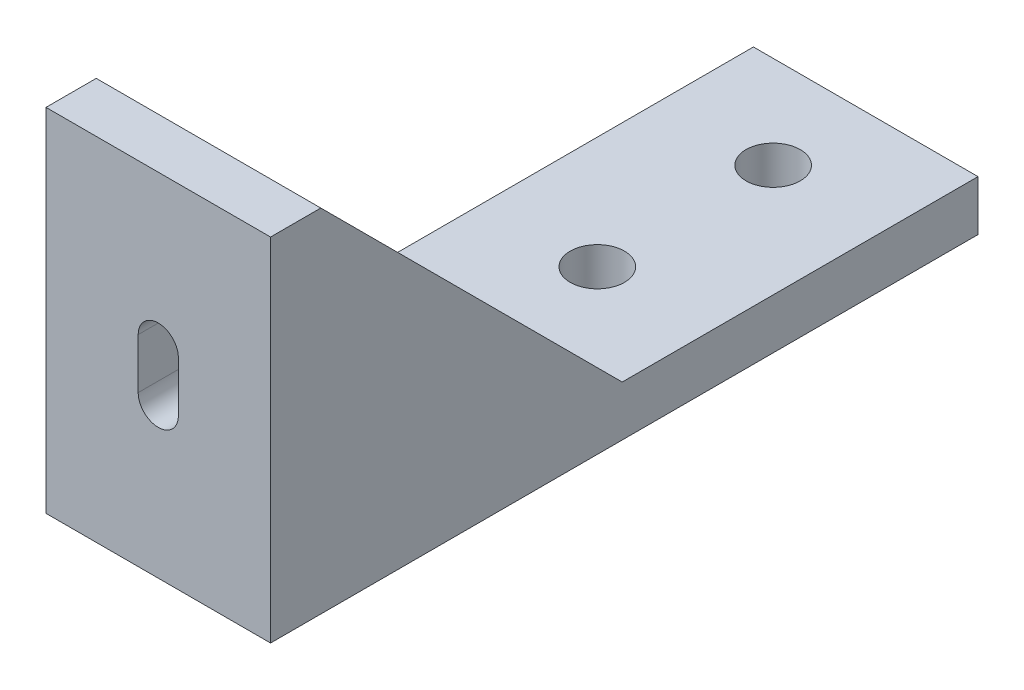
SolidWorks part; units mm, degrees
ref_plane "Front Plane" through (0, 0, 0) normal (0, 0, 1) x (1, 0, 0)
ref_plane "Top Plane" through (0, 0, 0) normal (0, 1, 0) x (1, 0, 0)
ref_plane "Right Plane" through (0, 0, 0) normal (1, 0, 0) x (0, 0, -1)
sketch "Sketch1" plane through (0, 0, 0) normal (0, 1, 0) x (1, 0, 0)
  line L0 (0.6663, -42.8738) -> (-10.5097, -42.8738)
  line L1 (-10.5097, -15.8168) -> (-10.5097, -42.8738)
  line L2 (0.6663, -42.8738) -> (11.8423, -42.8738)
  line L3 (11.8423, -42.8738) -> (11.8423, 42.5406)
  line L4 (11.8423, 42.5406) -> (-10.5097, 42.5406)
  line L5 (-10.5097, -15.8168) -> (-10.5097, 42.5406)
  circle A0 centre (0.6663, 31.3196) radius 2.7
  circle A1 centre (0.6663, 14.2508) radius 2.7
extrude "Boss-Extrude1" add sketch "Sketch1" along normal blind 5
sketch "Sketch2" plane through (0, 5, 0) normal (0, 1, 0) x (1, 0, 0)
  line L0 (-10.5097, 42.5406) -> (-10.5097, -42.8738) construction
  line L1 (11.8423, -42.8738) -> (-10.5097, -42.8738)
  line L2 (11.8423, -42.8738) -> (11.8423, -37.8738)
  line L3 (11.8423, -37.8738) -> (-10.5097, -37.8738)
  line L4 (-10.5097, -42.8738) -> (-10.5097, -37.8738)
extrude "Boss-Extrude2" add sketch "Sketch2" along normal blind 30
sketch "Sketch3" plane through (0, 0, 37.8738) normal (0, 0, -1) x (-1, 0, 0)
  line L0 (-11.8423, 35) -> (10.5097, 35) construction
  line L1 (-11.8423, 5) -> (-11.8423, 35)
  line L3 (-2.6663, 20) -> (-2.6663, 15)
  line L4 (1.3337, 20) -> (1.3337, 15)
  arc A0 (1.3337, 20) -> (-2.6663, 20) centre (-0.6663, 20) ccw
  arc A1 (-2.6663, 15) -> (1.3337, 15) centre (-0.6663, 15) ccw
  point P0 (-0.6663, 35)
  point P1 (-11.8423, 5)
  point P8 (-11.8423, 20)
  dimension "D1" = 5
  dimension "D2" = 4
extrude "Cut-Extrude1" cut sketch "Sketch3" against normal blind 5 contours A0
sketch "Sketch4" plane through (11.8423, 0, 0) normal (1, 0, 0) x (0, 0, -1)
  line L0 (-37.8738, 5) -> (42.5406, 5) construction
  line L2 (-37.8738, 35) -> (-37.8738, 5)
  line L3 (-37.8738, 5) -> (-7.8738, 5)
  line L5 (-37.8738, 35) -> (-7.8738, 5)
extrude "Boss-Extrude3" add sketch "Sketch4" against normal blind 2
sketch "Sketch5" plane through (-10.5097, 0, 0) normal (-1, 0, 0) x (0, 0, 1)
  line L0 (37.8738, 35) -> (7.8738, 5)
  line L1 (7.8738, 5) -> (37.8738, 5)
  line L2 (37.8738, 5) -> (37.8738, 35)
extrude "Boss-Extrude4" add sketch "Sketch5" against normal blind 2
sketch "Sketch7" plane through (0, 0, 0) normal (0, -1, 0) x (1, 0, 0)
  line L0 (-10.5097, -42.5406) -> (-10.5097, 42.8738) construction
  line L1 (11.8423, -42.5406) -> (-10.5097, -42.5406)
  line L2 (11.8423, -42.5406) -> (11.8423, -5.6331)
  line L3 (11.8423, -5.6331) -> (-10.5097, -5.6331)
  line L4 (-10.5097, -42.5406) -> (-10.5097, -5.6331)
extrude "Boss-Extrude5" add sketch "Sketch7" against normal up to surface (5 mm away) up to face at (0.6663, 5, 2.7702)
sketch "Sketch8" plane through (0, 0, 0) normal (0, -1, 0) x (1, 0, 0)
  line L0 (-10.5097, 42.8738) -> (11.8423, 42.8738) construction
  circle A0 centre (0.6663, -0.8262) radius 2.7
  circle A1 centre (0.6663, -18.3262) radius 2.7
  point P0 (0.6663, 42.8738)
  dimension "D1" = 5.4
  dimension "D2" = 5.4
  dimension "D4" = 61.2
  dimension "D3" = 43.7
extrude "Cut-Extrude2" cut sketch "Sketch8" against normal up to surface (5 mm away) up to face at (0.6663, 5, 2.7702)
sketch "Sketch9" plane through (0, 0, -42.5406) normal (0, 0, -1) x (-1, 0, 0)
  line L1 (-11.8423, 5) -> (10.5097, 5)
  line L2 (-11.8423, 5) -> (-11.8423, 0)
  line L3 (-11.8423, 0) -> (10.5097, 0)
  line L4 (10.5097, 5) -> (10.5097, 0)
extrude "Cut-Extrude3" cut sketch "Sketch9" against normal blind 15
